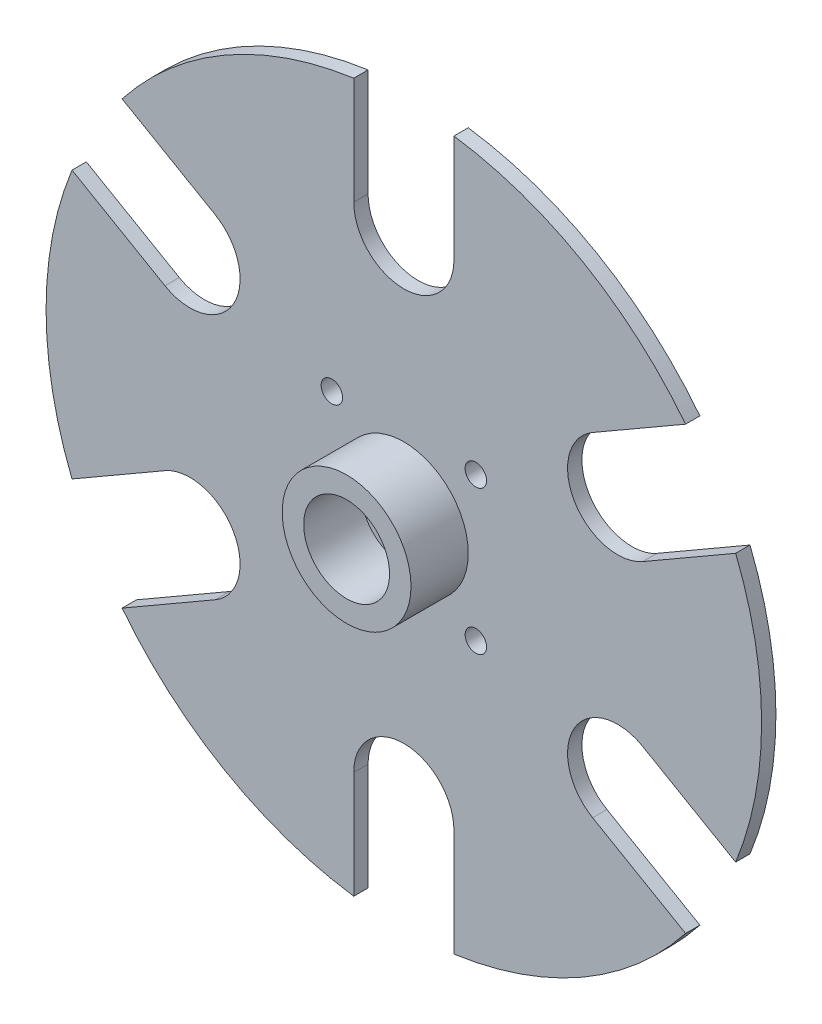
SolidWorks part; units mm, degrees
ref_plane "Front Plane" through (0, 0, 0) normal (0, 0, 1) x (1, 0, 0)
ref_plane "Top Plane" through (0, 0, 0) normal (0, 1, 0) x (1, 0, 0)
ref_plane "Right Plane" through (0, 0, 0) normal (1, 0, 0) x (0, 0, -1)
sketch "Sketch1" plane through (0, 0, 0) normal (0, 0, 1) x (1, 0, 0)
  line L0 (0, 0) -> (0, 22.0431) construction
  line L1 (0, 22.0431) -> (0, -27.0486) construction
  line L2 (0, -27.0486) -> (0, -2.5028) construction
  line L3 (0, 0) -> (34.3402, 0) construction
  line L4 (34.3402, 0) -> (-48.5021, 0) construction
  line L5 (0, 0) -> (-22.0431, 22.0431) construction
  circle A0 centre (0, 0) radius 6
  circle A1 centre (0, 0) radius 20
  circle A2 centre (-10.062, 10.062) radius 1.5
  circle A3 centre (10.062, 10.062) radius 1.5
  circle A4 centre (10.062, -10.062) radius 1.5
  circle A5 centre (-10.062, -10.062) radius 1.5
  dimension "D1" = 12
  dimension "D2" = 40
  dimension "D3" = 3
extrude "Boss-Extrude1" add sketch "Sketch1" along normal blind 5
sketch "Sketch2" plane through (0, 0, 5) normal (0, 0, 1) x (1, 0, 0)
  circle A0 centre (0, 0) radius 6
  circle A1 centre (0, 0) radius 9
  dimension "D1" = 3
extrude "Boss-Extrude2" add sketch "Sketch2" along normal blind 10
sketch "Sketch3" plane through (0, 0, 5) normal (0, 0, 1) x (1, 0, 0)
  circle A0 centre (0, 0) radius 50
  dimension "D1" = 100
extrude "Boss-Extrude3" add sketch "Sketch3" along normal blind 2
sketch "Sketch4" plane through (0, 0, 7) normal (0, 0, 1) x (1, 0, 0)
  line L0 (0, 0) -> (0, 27.5076) construction
  line L1 (-7, 49.5076) -> (-7, 34.5076)
  line L2 (39.3748, 30.816) -> (26.3844, 23.316)
  line L3 (7, 49.5076) -> (7, 34.5076)
  line L4 (0, 49.5076) -> (0, 50) construction
  line L5 (46.3748, 18.6916) -> (33.3844, 11.1916)
  line L6 (46.3748, -18.6916) -> (33.3844, -11.1916)
  line L7 (39.3748, -30.816) -> (26.3844, -23.316)
  line L8 (7, -49.5076) -> (7, -34.5076)
  line L9 (-7, -49.5076) -> (-7, -34.5076)
  line L10 (-39.3748, -30.816) -> (-26.3844, -23.316)
  line L11 (-46.3748, -18.6916) -> (-33.3844, -11.1916)
  line L12 (-46.3748, 18.6916) -> (-33.3844, 11.1916)
  line L13 (-39.3748, 30.816) -> (-26.3844, 23.316)
  circle A0 centre (0, 0) radius 50 construction
  arc A1 (7, 49.5076) -> (-7, 49.5076) centre (0, 0) ccw
  arc A2 (-7, 34.5076) -> (7, 34.5076) centre (0, 34.5076) ccw
  arc A3 (26.3844, 23.316) -> (33.3844, 11.1916) centre (29.8844, 17.2538) ccw
  arc A4 (46.3748, 18.6916) -> (39.3748, 30.816) centre (0, 0) ccw
  arc A5 (33.3844, -11.1916) -> (26.3844, -23.316) centre (29.8844, -17.2538) ccw
  arc A6 (39.3748, -30.816) -> (46.3748, -18.6916) centre (0, 0) ccw
  arc A7 (7, -34.5076) -> (-7, -34.5076) centre (0, -34.5076) ccw
  arc A8 (-7, -49.5076) -> (7, -49.5076) centre (0, 0) ccw
  arc A9 (-26.3844, -23.316) -> (-33.3844, -11.1916) centre (-29.8844, -17.2538) ccw
  arc A10 (-46.3748, -18.6916) -> (-39.3748, -30.816) centre (0, 0) ccw
  arc A11 (-33.3844, 11.1916) -> (-26.3844, 23.316) centre (-29.8844, 17.2538) ccw
  arc A12 (-39.3748, 30.816) -> (-46.3748, 18.6916) centre (0, 0) ccw
  point P11 (0, 34.5076)
  point P42 (0, 0)
  dimension "D1" = 7
  dimension "D2" = 15
  dimension "D3" = 6
extrude "Cut-Extrude1" cut sketch "Sketch4" against normal blind 2
sketch "Sketch5" plane through (0, 0, 0) normal (0, 0, -1) x (-1, 0, 0)
  circle A0 centre (-10.062, 10.062) radius 1.5
  circle A1 centre (-10.062, -10.062) radius 1.5
  circle A2 centre (10.062, 10.062) radius 1.5
  circle A3 centre (10.062, -10.062) radius 1.5
extrude "Cut-Extrude2" cut sketch "Sketch5" against normal through all both and the other way through all
